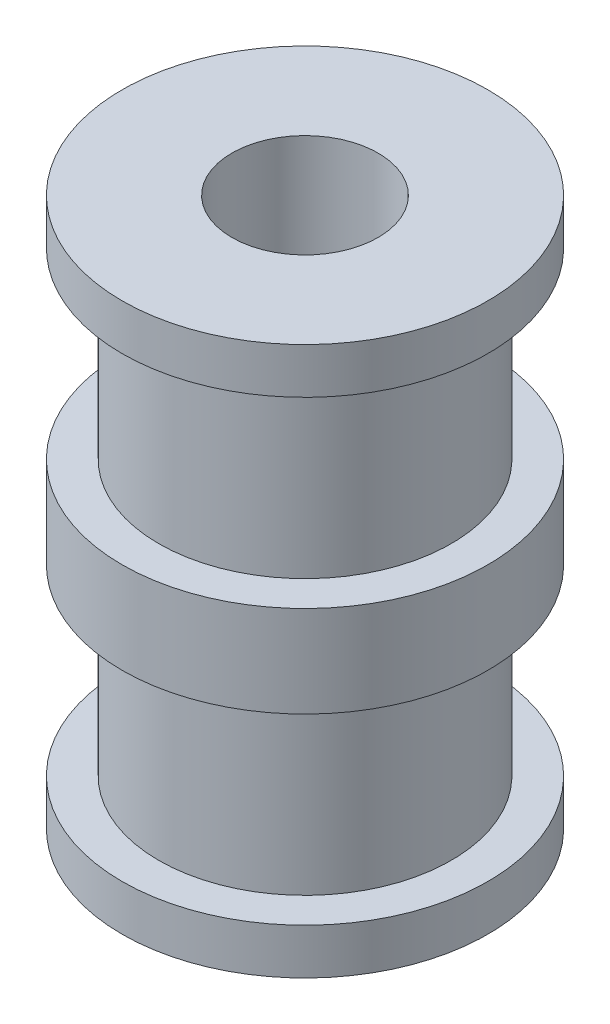
SolidWorks part; units mm, degrees
ref_plane "Plan de face" through (0, 0, 0) normal (0, 0, 1) x (1, 0, 0)
ref_plane "Plan de dessus" through (0, 0, 0) normal (0, 1, 0) x (1, 0, 0)
ref_plane "Plan de droite" through (0, 0, 0) normal (1, 0, 0) x (0, 0, -1)
sketch "Esquisse1" plane through (0, 0, 0) normal (0, 1, 0) x (1, 0, 0)
  circle A0 centre (0, 0) radius 2
  circle A1 centre (0, 0) radius 4
  dimension "D1" = 4
  dimension "D2" = 8
extrude "Boss.-Extru.1" add sketch "Esquisse1" along normal blind 15
sketch "Esquisse2" plane through (0, 0, 0) normal (0, 1, 0) x (1, 0, 0)
  circle A0 centre (0, 0) radius 2
  circle A1 centre (0, 0) radius 5
  dimension "D1" = 10
extrude "Boss.-Extru.2" add sketch "Esquisse2" along normal blind 1.25
ref_plane "Plan2" through (0, 6.25, 0) normal (0, 1, 0) x (1, 0, 0)
sketch "Esquisse3" plane through (0, 6.25, 0) normal (0, 1, 0) x (1, 0, 0)
  circle A0 centre (0, 0) radius 2
  circle A1 centre (0, 0) radius 5
extrude "Boss.-Extru.3" add sketch "Esquisse3" along normal blind 2.5
sketch "Esquisse4" plane through (0, 15, 0) normal (0, 1, 0) x (1, 0, 0)
  circle A0 centre (0, 0) radius 2
  circle A1 centre (0, 0) radius 5
sketch "Esquisse5" plane through (0, 15, 0) normal (0, 1, 0) x (1, 0, 0)
  circle A1 centre (0, 0) radius 2
  circle A2 centre (0, 0) radius 5
extrude "Boss.-Extru.5" add sketch "Esquisse5" against normal blind 1.25
